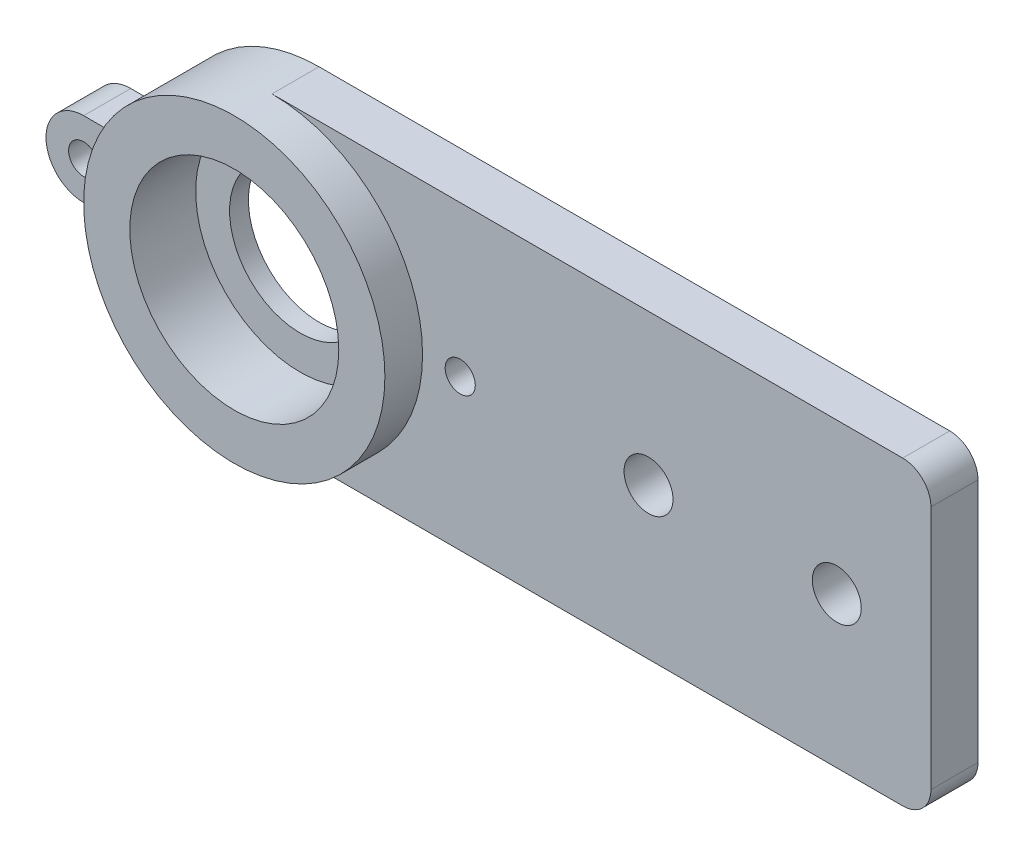
SolidWorks part; units mm, degrees
material "PET"
ref_plane "Front Plane" through (0, 0, 0) normal (0, 0, 1) x (1, 0, 0)
ref_plane "Top Plane" through (0, 0, 0) normal (0, 1, 0) x (1, 0, 0)
ref_plane "Right Plane" through (0, 0, 0) normal (1, 0, 0) x (0, 0, -1)
sketch "Sketch2" plane through (0, 0, 0) normal (0, 0, 1) x (1, 0, 0)
  line L0 (60, -24) -> (60, 16) construction
  line L1 (30, 16) -> (70, 16)
  line L2 (30, 16) -> (30, -4) construction
  line L3 (30, -4) -> (50, -4) construction
  line L4 (70, 16) -> (70, -4)
  line L6 (50, -4) -> (50, -24) construction
  line L7 (50, -24) -> (70, -24)
  line L8 (70, -4) -> (70, -24)
  line L9 (70, 6) -> (30, 6) construction
  line L10 (0, 16) -> (30, 16)
  line L11 (0, -16) -> (50, -24)
  circle A0 centre (0, 0) radius 11.1
  circle A1 centre (0, 0) radius 16
  circle A2 centre (40, 6) radius 2.6
  circle A3 centre (60, 6) radius 2.6
  circle A4 centre (60, -14) radius 2.6
  point P21 (50, -14)
  dimension "D1" = 22.2
  dimension "D2" = 32
  dimension "D3" = 5.2
  dimension "D4" = 5.2
  dimension "D5" = 5.2
  dimension "D6" = 20
  dimension "D7" = 20
  dimension "D8" = 20
  dimension "D9" = 40
  dimension "D10" = 20
  dimension "D11" = 30
sketch "Sketch3" plane through (0, 0, 0) normal (0, 0, 1) x (1, 0, 0)
  line L0 (60, -24) -> (60, 16) construction
  line L1 (30, 16) -> (70, 16)
  line L2 (30, 16) -> (30, -4) construction
  line L3 (30, -4) -> (50, -4) construction
  line L4 (70, 16) -> (70, -4)
  line L5 (-20, 4) -> (-15.4919, 4)
  line L6 (50, -4) -> (50, -24) construction
  line L7 (50, -24) -> (70, -24)
  line L8 (70, -4) -> (70, -24)
  line L9 (70, 6) -> (30, 6) construction
  line L10 (0, 16) -> (30, 16)
  line L11 (0, -16) -> (50, -24)
  line L12 (-20, -4) -> (-15.4919, -4)
  line L13 (-15.4919, 4) -> (-15.4919, -4)
  circle A0 centre (0, 0) radius 7.5
  arc A1 (-15.4919, -4) -> (-15.4919, 4) centre (0, 0) ccw
  circle A2 centre (40, 6) radius 2.6
  circle A3 centre (60, 6) radius 2.6
  circle A4 centre (60, -14) radius 2.6
  circle A5 centre (-20, 0) radius 1.6
  arc A6 (-20, 4) -> (-20, -4) centre (-20, 0) ccw
  point P21 (50, -14)
  dimension "D1" = 15
  dimension "D2" = 32
  dimension "D3" = 5.2
  dimension "D4" = 5.2
  dimension "D5" = 5.2
  dimension "D12" = 3.2
  dimension "D13" = 8
  dimension "D6" = 20
  dimension "D7" = 20
  dimension "D8" = 20
  dimension "D9" = 40
  dimension "D10" = 20
  dimension "D11" = 30
extrude "Boss-Extrude3" add sketch "Sketch3" along normal blind 2 contours A1 A0
extrude "Boss-Extrude4" add sketch "Sketch2" along normal blind 9 contours A1 A0
sketch "Sketch4" plane through (0, 0, 0) normal (0, 0, 1) x (1, 0, 0)
  line L1 (30, 16) -> (70, 16)
  line L2 (30, 16) -> (30, -16) construction
  line L4 (70, 16) -> (70, -16)
  line L5 (-20, 4) -> (-15.4919, 4)
  line L9 (70, 0) -> (30, 0) construction
  line L10 (0, 16) -> (30, 16)
  line L12 (-20, -4) -> (-15.1432, -5.1656)
  line L13 (0, -16) -> (70, -16)
  circle A0 centre (0, 0) radius 7.5
  arc A1 (-15.1432, -5.1656) -> (-15.4919, 4) centre (0, 0) ccw
  circle A2 centre (40, 0) radius 2.6
  circle A3 centre (60, 0) radius 2.6
  circle A5 centre (-20, 0) radius 1.6
  arc A6 (-20, 4) -> (-20, -4) centre (-20, 0) ccw
  point P2 (50, -23.876)
  point P3 (50, -16)
  point P8 (70, -16)
  point P9 (70, -4)
  point P11 (69.9867, 14.9671)
  point P14 (70, -15.6572)
  point P15 (70, -4)
  point P16 (70, -4)
  point P17 (51.8412, -4)
  point P18 (44.2041, 0)
  dimension "D1" = 15
  dimension "D2" = 32
  dimension "D3" = 5.2
  dimension "D4" = 5.2
  dimension "D5" = 10
  dimension "D12" = 3.2
  dimension "D13" = 8
  dimension "D6" = 10
  dimension "D8" = 20
  dimension "D9" = 40
  dimension "D11" = 30
extrude "Boss-Extrude5" add sketch "Sketch4" along normal blind 5
fillet "Fillet3" radius 3 2 edges at (70, 16, 2.5) (70, -16, 2.5)
sketch "Sketch5" plane through (0, 0, 0) normal (0, 0, 1) x (1, 0, 0)
  line L0 (60, -24) -> (60, 16) construction
  line L1 (30, 16) -> (70, 16)
  line L2 (30, 16) -> (30, -4) construction
  line L3 (30, -4) -> (50, -4) construction
  line L4 (70, 16) -> (70, -4)
  line L5 (-20, 4) -> (-15.4919, 4)
  line L6 (50, -4) -> (50, -24) construction
  line L7 (50, -24) -> (70, -24)
  line L8 (70, -4) -> (70, -24)
  line L9 (70, 6) -> (30, 6) construction
  line L10 (0, 16) -> (30, 16)
  line L11 (0, -16) -> (50, -24)
  line L12 (-20, -4) -> (-15.4919, -4)
  line L13 (-15.4919, 4) -> (-15.4919, -4)
  circle A0 centre (0, 0) radius 7.5
  arc A1 (-15.4919, -4) -> (-15.4919, 4) centre (0, 0) ccw
  circle A2 centre (40, 6) radius 2.6
  circle A3 centre (60, 6) radius 2.6
  circle A4 centre (60, -14) radius 2.6
  circle A5 centre (-20, 0) radius 1.6
  arc A6 (-20, 4) -> (-20, -4) centre (-20, 0) ccw
  point P21 (50, -14)
  dimension "D1" = 15
  dimension "D2" = 32
  dimension "D3" = 5.2
  dimension "D4" = 5.2
  dimension "D5" = 5.2
  dimension "D12" = 3.2
  dimension "D13" = 8
  dimension "D6" = 20
  dimension "D7" = 20
  dimension "D8" = 20
  dimension "D9" = 40
  dimension "D10" = 20
  dimension "D11" = 30
  dimension "D14" = 20
extrude "Boss-Extrude6" add sketch "Sketch5" along normal blind 5 contours L5 A6 L12 L13 A5
sketch "Sketch6" plane through (0, 0, 5) normal (0, 0, 1) x (1, 0, 0)
  circle A0 centre (20, 0) radius 1.6
  dimension "D1" = 3.2
  dimension "D2" = 20
extrude "Cut-Extrude1" cut sketch "Sketch6" against normal blind 10 contours A0
